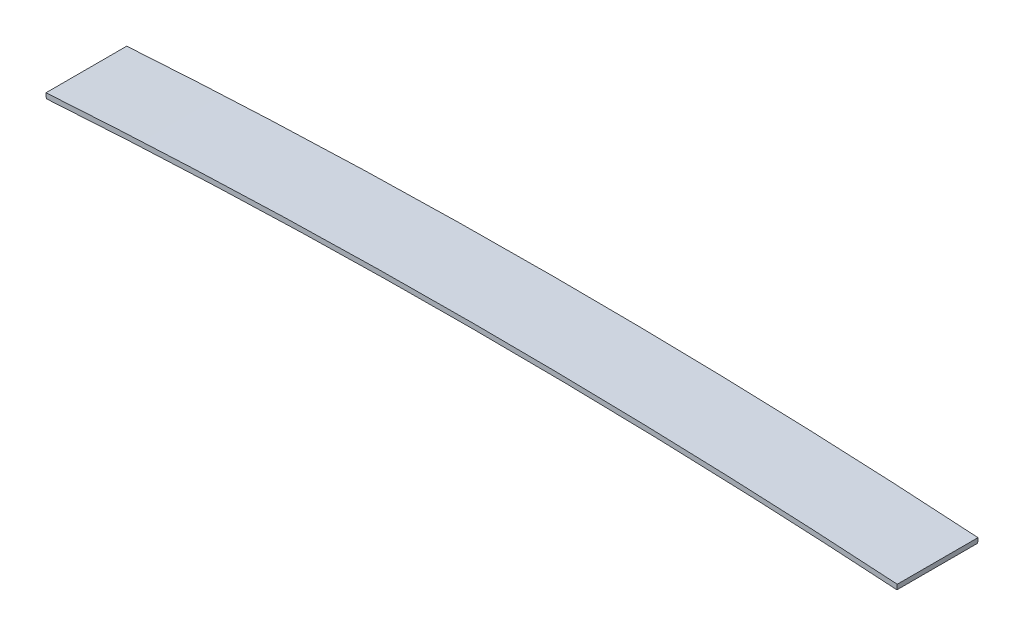
SolidWorks part; units mm, degrees
ref_plane "Спереди" through (0, 0, 0) normal (0, 0, 1) x (1, 0, 0)
ref_plane "Сверху" through (0, 0, 0) normal (0, 1, 0) x (1, 0, 0)
ref_plane "Справа" through (0, 0, 0) normal (1, 0, 0) x (0, 0, -1)
sketch "Model" plane through (0, 0, 0) normal (0, 0, 1) x (1, 0, 0)
  line L0 (84.2978, 0) -> (84.3305, 0.4989)
  line L1 (-0.0327, 0.4989) -> (0, 0)
  spline S0 degree 3 poles (0, 0) (28.0993, 1.8424) (56.1985, 1.8424) (84.2978, 0) knots 0 0 0 0 1 1 1 1
  spline S1 degree 3 poles (84.3305, 0.4989) (56.2095, 2.3427) (28.0883, 2.3427) (-0.0327, 0.4989) knots 0 0 0 0 1 1 1 1
extrude "Бобышка-Вытянуть1" add sketch "Model" against normal blind 8
